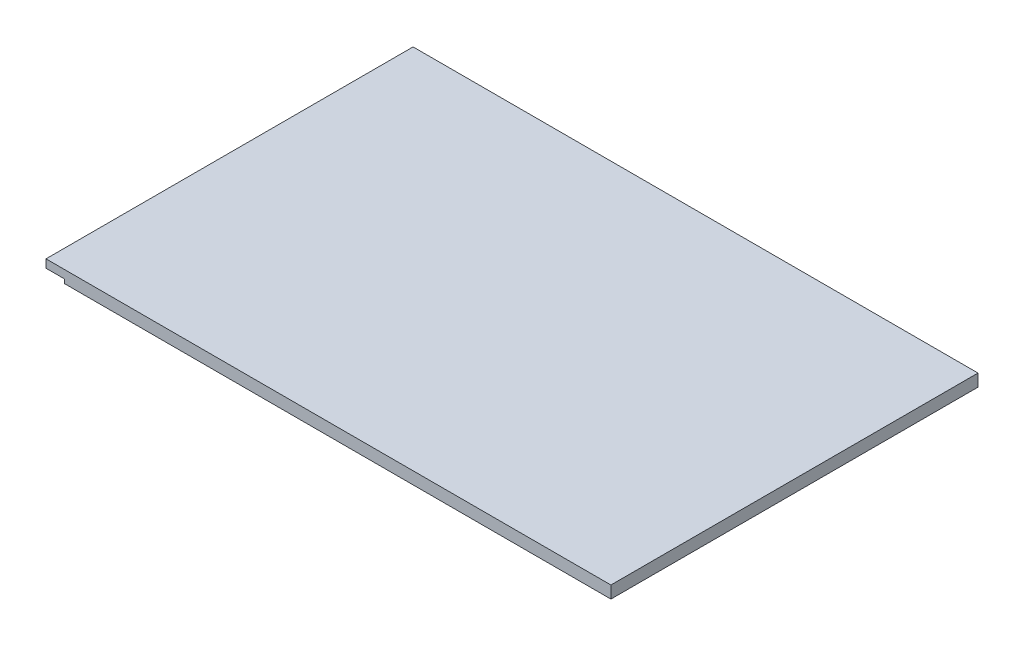
SolidWorks part; units mm, degrees
material "Teak"
ref_plane "Front Plane" through (0, 0, 0) normal (0, 0, 1) x (1, 0, 0)
ref_plane "Top Plane" through (0, 0, 0) normal (0, 1, 0) x (1, 0, 0)
ref_plane "Right Plane" through (0, 0, 0) normal (1, 0, 0) x (0, 0, -1)
sketch "Sketch1" plane through (0, 0, 0) normal (0, 1, 0) x (1, 0, 0)
  line L1 (335, -225) -> (-335, -225)
  line L2 (335, -225) -> (335, 225)
  line L3 (335, 225) -> (-335, 225)
  line L4 (-335, -225) -> (-335, 225)
  line L5 (335, -225) -> (-335, 225) construction
  line L6 (335, 225) -> (-335, -225) construction
  point P0 (0, 0)
  dimension "D1" = 670
  dimension "D2" = 450
extrude "Boss-Extrude1" add sketch "Sketch1" along normal mid plane 15
sketch "Sketch2" plane through (0, -7.5, 0) normal (0, -1, 0) x (1, 0, 0)
  line L0 (0, -225) -> (0, 225) construction
  line L1 (-335, 225) -> (335, 225) construction
  line L2 (-335, 0) -> (335, 0) construction
  line L3 (335, 225) -> (335, -225) construction
  line L4 (-328, 0) -> (-328, -225) construction
  line L5 (335, -225) -> (-335, -225) construction
  line L6 (-335, -225) -> (-335, 225) construction
  circle A0 centre (-328, -150) radius 2.5
  circle A1 centre (-328, -110) radius 2.5
  circle A2 centre (-313, -130) radius 2.5
  circle A3 centre (-328, 150) radius 2.5
  circle A4 centre (-313, 130) radius 2.5
  circle A5 centre (-328, 110) radius 2.5
  circle A6 centre (328, 150) radius 2.5
  circle A7 centre (328, 110) radius 2.5
  circle A8 centre (313, 130) radius 2.5
  circle A9 centre (328, -150) radius 2.5
  circle A10 centre (313, -130) radius 2.5
  circle A11 centre (328, -110) radius 2.5
  point P6 (0, 0)
  point P11 (0, 0)
  dimension "D6" = 5
  dimension "D1" = 7
  dimension "D2" = 40
  dimension "D3" = 20
  dimension "D4" = 15
  dimension "D5" = 75
extrude "Cut-Extrude1" cut sketch "Sketch2" against normal blind 10
sketch "Sketch3" plane through (0, 7.5, 0) normal (0, 1, 0) x (1, 0, 0)
  line L0 (-335, -225) -> (335, -225) construction
  line L1 (-335, 225) -> (-357.5, 225)
  line L2 (-335, 225) -> (-335, -225)
  line L3 (-335, -225) -> (-357.5, -225)
  line L4 (-357.5, 225) -> (-357.5, -225)
  dimension "D1" = 22.5
extrude "Boss-Extrude2" add sketch "Sketch3" against normal blind 10
sketch "Sketch4" plane through (0, -7.5, 0) normal (0, -1, 0) x (-1, 0, 0)
  circle A1 centre (313, 0) radius 2.5
  circle A2 centre (328, -20) radius 2.5
  circle A3 centre (328, 20) radius 2.5
  dimension "D1" = 5
  dimension "D2" = 5
  dimension "D3" = 5
extrude "Cut-Extrude2" cut sketch "Sketch4" against normal blind 10
